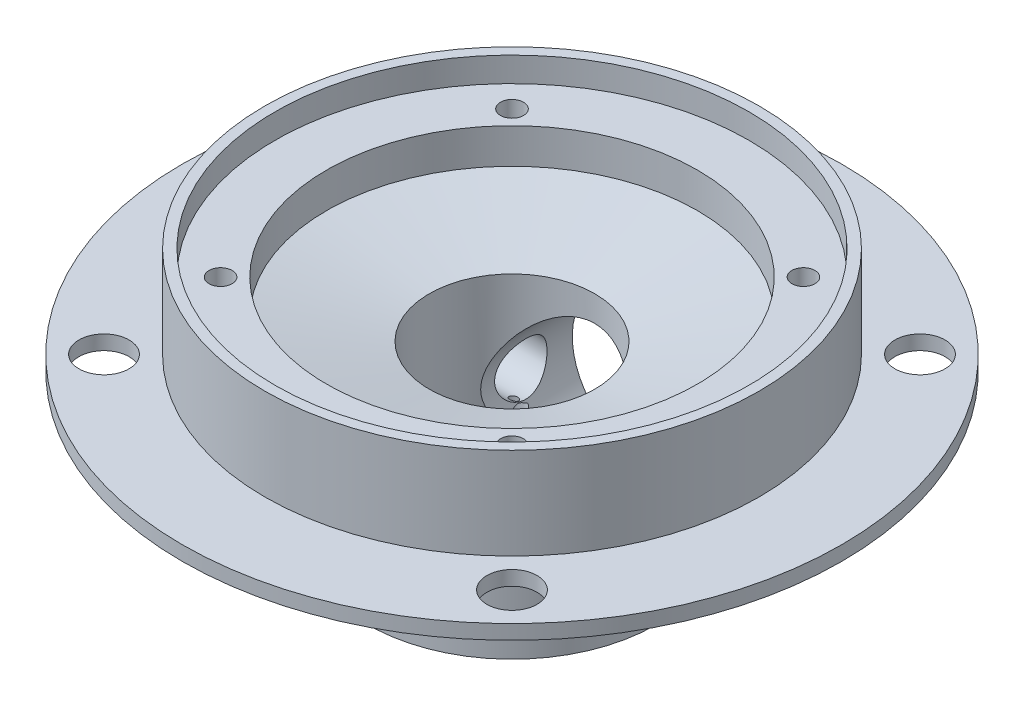
SolidWorks part; units mm, degrees
ref_plane "Front Plane" through (0, 0, 0) normal (0, 0, 1) x (1, 0, 0)
ref_plane "Top Plane" through (0, 0, 0) normal (0, 1, 0) x (1, 0, 0)
ref_plane "Right Plane" through (0, 0, 0) normal (1, 0, 0) x (0, 0, -1)
sketch "Sketch1" plane through (0, 0, 0) normal (0, 0, 1) x (1, 0, 0)
  line L0 (0, -1.3892) -> (0, 8.5257) construction
  line L1 (6.3754, 0) -> (12.7508, 0) construction
  line L2 (12.7508, 0) -> (12.7508, 8.8796) construction
  line L3 (12.7508, 8.8796) -> (15.0812, 8.8796)
  line L4 (15.0812, 8.8796) -> (15.0812, 9.1336)
  line L5 (15.0812, 9.1336) -> (25.4, 9.1336)
  line L6 (25.4, 9.1336) -> (25.4, 10.2512)
  line L7 (25.4, 10.2512) -> (19.0373, 10.2512)
  line L8 (19.0373, 10.2512) -> (19.0373, 17.3124)
  line L9 (19.0373, 17.3124) -> (18.2562, 17.3124)
  line L10 (18.2562, 17.3124) -> (18.2562, 15.4074)
  line L11 (18.2562, 15.4074) -> (14.2875, 15.4074)
  line L12 (14.2875, 15.4074) -> (14.2875, 12.7)
  line L13 (14.2875, 12.7) -> (6.3754, 11.1125)
  line L14 (6.3754, 11.1125) -> (6.3754, 8.8796)
  line L15 (12.7508, 8.8796) -> (6.3754, 8.8796)
  line L16 (6.3754, 8.8796) -> (6.3754, 0) construction
  dimension "D1" = 7.0612
  dimension "D2" = 8.1788
  dimension "D3" = 8.4328
  dimension "D4" = 17.3124
  dimension "D5" = 25.4
  dimension "D6" = 30.1625
  dimension "D7" = 12.7508
  dimension "D8" = 38.0746
  dimension "D9" = 36.5125
  dimension "D10" = 28.575
  dimension "D11" = 12.7508
  dimension "D12" = 1.905
  dimension "D13" = 1.5875
  dimension "D14" = 11.1125
revolve "Revolve1" add sketch "Sketch1" angle 360 about L0
sketch "Sketch2" plane through (0, 8.8796, 0) normal (0, -1, 0) x (1, 0, 0)
  line L0 (-11.1125, 0) -> (-11.1125, -10.1959)
  line L1 (-11.1125, -10.1959) -> (11.1125, -10.1959)
  line L2 (11.1125, -10.1959) -> (11.1125, 0)
  arc A0 (-11.1125, 0) -> (11.1125, 0) centre (0, 0) cw
  circle A2 centre (0, 0) radius 6.3754 construction
  circle A4 centre (0, 0) radius 15.0812 construction
  circle A5 centre (0, 0) radius 15.0812 construction
  circle A6 centre (0, 0) radius 6.3754
  dimension "D1" = 11.1125
extrude "Boss-Extrude1" add sketch "Sketch2" along normal blind 11.1125
sketch "Sketch3" plane through (0, 0, -10.1959) normal (0, 0, -1) x (-1, 0, 0)
  line L0 (-25.4, 9.1336) -> (25.4, 9.1336) construction
  circle A0 centre (0, 3.5773) radius 5.5499
  dimension "D1" = 11.0998
  dimension "D2" = 5.5562
extrude "Cut-Extrude1" cut sketch "Sketch3" against normal up to surface and the other way through all
sketch "Sketch4" plane through (-11.1125, 0, 0) normal (-1, 0, 0) x (0, 0, 1)
  line L0 (-25.4, 9.1336) -> (25.4, 9.1336) construction
  point P0 (-6.2272, 3.5773)
  dimension "D1" = 5.5562
  dimension "D2" = 3.9688
hole_wizard "#10-32 Tapped Hole3" positions "Sketch4" profile "Sketch5" tap size "#10-32" standard "ANSI Inch" end condition through all
sketch "Sketch5" plane through (-11.1125, 3.5773, -6.2272) normal (0, 1, 0) x (0, 0, 1)
  line L0 (0, 0) -> (0, 36.5125)
  line L1 (0, 36.5125) -> (2.0193, 36.5125)
  line L2 (2.0193, 36.5125) -> (2.0193, 0)
  line L5 (2.0193, 0) -> (0, 0)
  line L11 (0, -6.35) -> (0, 107.95) construction
  dimension "Thru Tap Drill Dia." = 4.0386
  dimension "Thru Tap Drill Depth" = 36.5125
cosmetic thread "Hole Thread1" parameters "D2"=4.826
sketch "Sketch7" plane through (0, 10.2512, 0) normal (0, 1, 0) x (1, 0, 0)
  line L0 (0, 0) -> (15.7154, 15.7154) construction
  line L1 (0, 0) -> (34.3816, 0) construction
  line L2 (0, 0) -> (15.7154, 15.7154) construction
  line L3 (0, 0) -> (15.7154, -15.7154) construction
  point P6 (15.7154, 15.7154)
  point P8 (15.7154, -15.7154)
  point P9 (-15.7154, -15.7154)
  point P10 (-15.7154, 15.7154)
  dimension "D1" = 45
  dimension "D2" = 22.225
  dimension "D4" = 90
  dimension "D5" = 22.225
  dimension "D3" = 4
hole_wizard "#24 (0.152) Diameter Hole1" positions "Sketch7" profile "Sketch8" hole size "#24" standard "ANSI Inch" end condition up to next
sketch "Sketch8" plane through (-15.7154, 10.2512, -15.7154) normal (1, 0, 0) x (0, 0, 1)
  line L0 (0, 0) -> (0, 1.1176)
  line L1 (0, 1.1176) -> (1.9304, 1.1176)
  line L2 (1.9304, 1.1176) -> (1.9304, 0)
  line L5 (1.9304, 0) -> (0, 0)
  line L11 (0, -6.35) -> (0, 107.95) construction
  dimension "Thru Hole Dia." = 3.8608
  dimension "Thru Hole Depth" = 1.1176
sketch "Sketch9" plane through (0, 15.4074, 0) normal (0, 1, 0) x (1, 0, 0)
  line L0 (0, 0) -> (32.6573, 0) construction
  line L1 (0, 0) -> (11.2253, 11.2253) construction
  line L2 (0, 0) -> (11.2253, 11.2253) construction
  point P8 (11.2253, 11.2253)
  point P11 (11.2253, -11.2253)
  point P12 (-11.2253, -11.2253)
  point P13 (-11.2253, 11.2253)
  dimension "D1" = 45
  dimension "D2" = 15.875
  dimension "D4" = 15.875
  dimension "D3" = 4
hole_wizard "#2-56 Tapped Hole1" positions "Sketch9" profile "Sketch10" tap size "#2-56" standard "ANSI Inch"
sketch "Sketch10" plane through (-11.2253, 15.4074, -11.2253) normal (1, 0, 0) x (0, 0, 1)
  line L0 (0, 0) -> (0, 4.5982)
  line L1 (0, 4.5982) -> (0.889, 4.064)
  line L2 (0.889, 4.064) -> (0.889, 0)
  line L5 (0.889, 0) -> (0, 0)
  line L10 (0, 4.5982) -> (-0.889, 4.064) construction
  line L11 (0, -6.35) -> (0, 107.95) construction
  dimension "Tap Drill Dia." = 1.778
  dimension "Tap Drill Depth" = 4.064
  dimension "Drill Angle" = 118
cosmetic thread "Hole Thread2" parameters "D1"=4.318, "D2"=2.1844
cosmetic thread "Hole Thread3" parameters "D1"=4.318, "D2"=2.1844
cosmetic thread "Hole Thread4" parameters "D1"=4.318, "D2"=2.1844
cosmetic thread "Hole Thread5" parameters "D1"=4.318, "D2"=2.1844
sketch "Sketch11" plane through (0, -2.2329, 0) normal (0, -1, 0) x (1, 0, 0)
  line L0 (0, 0) -> (33.5386, 0) construction
  line L1 (0, 0) -> (5.6127, 5.6127) construction
  line L2 (0, 0) -> (5.6127, 5.6127) construction
  point P7 (5.6127, 5.6127)
  point P10 (5.6127, -5.6127)
  point P11 (-5.6127, -5.6127)
  point P12 (-5.6127, 5.6127)
  dimension "D1" = 45
  dimension "D2" = 7.9375
  dimension "D4" = 7.9375
  dimension "D3" = 4
hole_wizard "#2-56 Tapped Hole2" positions "Sketch11" profile "Sketch12" tap size "#2-56" standard "ANSI Inch"
sketch "Sketch12" plane through (-5.6127, -2.2329, 5.6127) normal (1, 0, 0) x (0, 0, -1)
  line L0 (0, 0) -> (0, 4.064)
  line L1 (0, 4.064) -> (0.889, 3.5298)
  line L2 (0.889, 3.5298) -> (0.889, 0)
  line L5 (0.889, 0) -> (0, 0)
  line L10 (0, 4.064) -> (-0.889, 3.5298) construction
  line L11 (0, -6.35) -> (0, 107.95) construction
  dimension "Tap Drill Dia." = 1.778
  dimension "Tap Drill Depth" = 4.064
  dimension "Drill Angle" = 118
cosmetic thread "Hole Thread6" parameters "D1"=4.318, "D2"=2.1844
cosmetic thread "Hole Thread7" parameters "D1"=4.318, "D2"=2.1844
cosmetic thread "Hole Thread8" parameters "D1"=4.318, "D2"=2.1844
cosmetic thread "Hole Thread9" parameters "D1"=4.318, "D2"=2.1844
